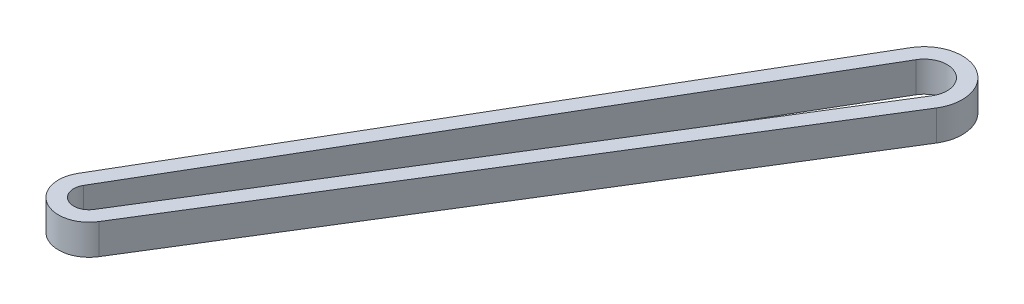
SolidWorks part; units mm, degrees
ref_plane "Front Plane" through (0, 0, 0) normal (0, 0, 1) x (1, 0, 0)
ref_plane "Top Plane" through (0, 0, 0) normal (0, 1, 0) x (1, 0, 0)
ref_plane "Right Plane" through (0, 0, 0) normal (1, 0, 0) x (0, 0, -1)
sketch "Sketch1" plane through (0, 0, 0) normal (0, 1, 0) x (1, 0, 0)
  line L0 (-61.4749, -81.86) -> (39.5573, 90.727)
  line L1 (-52.8448, -86.912) -> (50.3448, 84.412) construction
  line L2 (-44.3438, -92.1781) -> (60.9711, 77.8293)
  line L3 (-57.1599, -84.386) -> (43.8723, 88.201)
  line L4 (-48.5943, -89.545) -> (56.7206, 80.4623)
  arc A0 (60.9711, 77.8293) -> (39.5573, 90.727) centre (50.3448, 84.412) ccw
  arc A1 (-61.4749, -81.86) -> (-44.3438, -92.1781) centre (-52.8448, -86.912) ccw
  arc A2 (-57.1599, -84.386) -> (-48.5943, -89.545) centre (-52.8448, -86.912) ccw
  arc A3 (56.7206, 80.4623) -> (43.8723, 88.201) centre (50.3448, 84.412) ccw
extrude "Boss-Extrude1" add sketch "Sketch1" along normal blind 10
